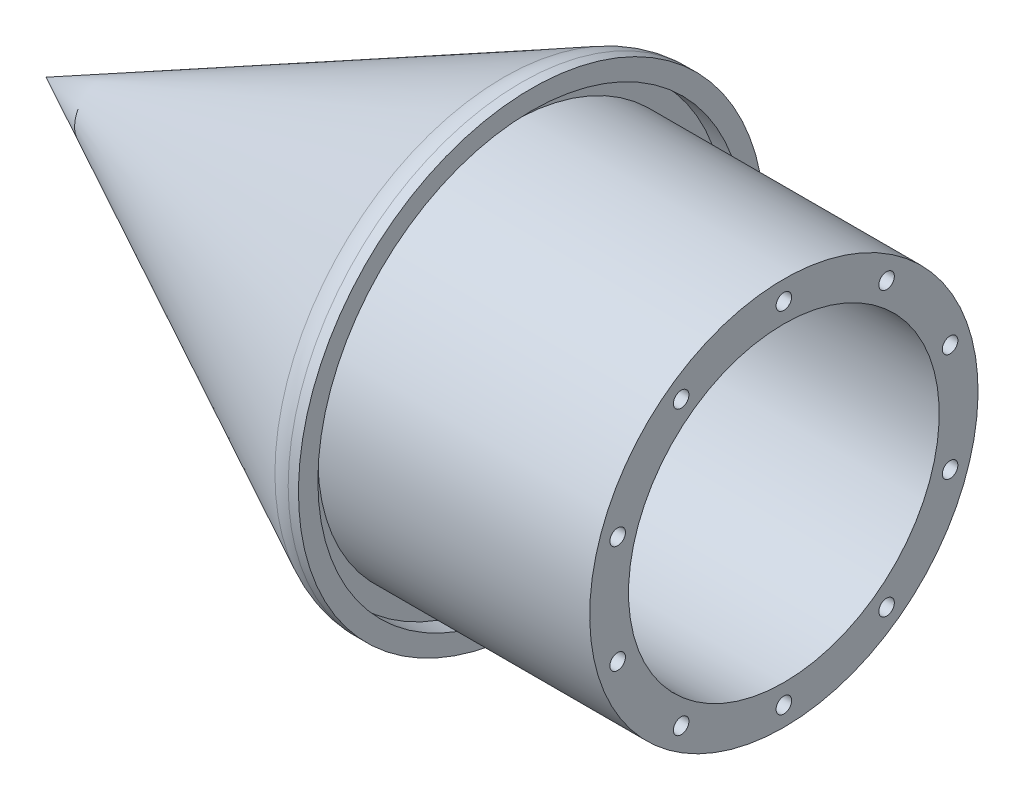
SolidWorks part; units mm, degrees
ref_plane "Front Plane" through (0, 0, 0) normal (0, 0, 1) x (1, 0, 0)
ref_plane "Top Plane" through (0, 0, 0) normal (0, 1, 0) x (1, 0, 0)
ref_plane "Right Plane" through (0, 0, 0) normal (1, 0, 0) x (0, 0, -1)
sketch "Sketch1" plane through (0, 0, 0) normal (0, 0, 1) x (1, 0, 0)
  line L0 (-170, 0) -> (129.1304, 0) construction
  line L1 (0, 0) -> (0, 40)
  line L2 (0, 40) -> (-80, 40)
  line L3 (-80, 40) -> (-80, 45)
  line L4 (-80, 45) -> (-170, 0)
  line L5 (0, 50) -> (-70, 50)
  line L6 (-70, 50) -> (-70, 55)
  line L7 (-70, 55) -> (-65, 55)
  line L8 (-65, 55) -> (-65, 60)
  line L9 (-65, 60) -> (-70, 60)
  line L10 (-70, 60) -> (-190, 0)
  line L11 (0, 50) -> (0, 40)
  line L12 (-170, 0) -> (-190, 0)
  dimension "D1" = 40
  dimension "D2" = 80
  dimension "D3" = 5
  dimension "D4" = 170
  dimension "D5" = 10
  dimension "D6" = 70
  dimension "D7" = 5
  dimension "D8" = 5
  dimension "D9" = 5
revolve "Revolve1" add sketch "Sketch1" angle 360 about L0
sketch "Sketch2" plane through (0, 0, 0) normal (1, 0, 0) x (0, 0, -1)
  circle A0 centre (0, 45) radius 2
  circle A1 centre (26.4503, 36.4058) radius 2
  circle A2 centre (42.7975, 13.9058) radius 2
  circle A3 centre (42.7975, -13.9058) radius 2
  circle A4 centre (26.4503, -36.4058) radius 2
  circle A5 centre (0, -45) radius 2
  circle A6 centre (-26.4503, -36.4058) radius 2
  circle A7 centre (-42.7975, -13.9058) radius 2
  circle A8 centre (-42.7975, 13.9058) radius 2
  circle A9 centre (-26.4503, 36.4058) radius 2
  point P24 (0, 0)
  dimension "D2" = 4
  dimension "D1" = 45
  dimension "D3" = 10
extrude "Cut-Extrude1" cut sketch "Sketch2" against normal blind 20
fillet "Fillet1" radius 10 1 edges at (-70, -60, 0)
